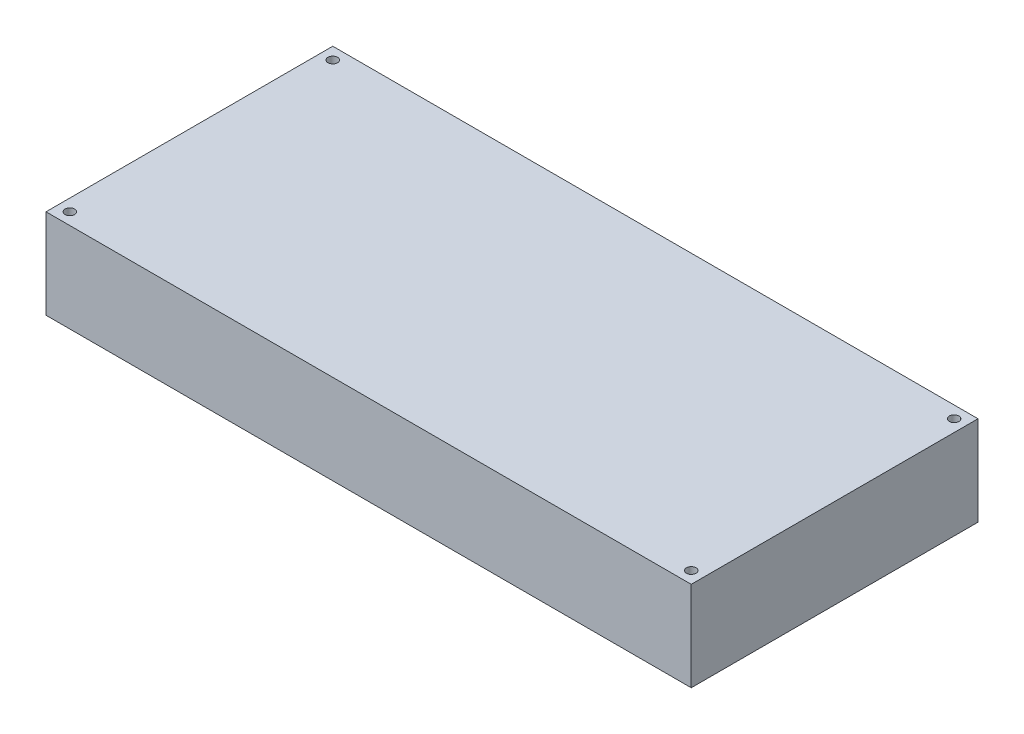
SolidWorks part; units mm, degrees
ref_plane "前视基准面" through (0, 0, 0) normal (0, 0, 1) x (1, 0, 0)
ref_plane "上视基准面" through (0, 0, 0) normal (0, 1, 0) x (1, 0, 0)
ref_plane "右视基准面" through (0, 0, 0) normal (1, 0, 0) x (0, 0, -1)
sketch "草图1" plane through (0, 0, 0) normal (0, 1, 0) x (1, 0, 0)
  line L0 (0, 0) -> (0, -29.456) construction
  line L1 (-54, 24) -> (54, 24)
  line L2 (-54, 24) -> (-54, -24)
  line L3 (-54, -24) -> (54, -24)
  line L4 (54, 24) -> (54, -24)
  line L5 (-54, 24) -> (54, -24) construction
  line L6 (-54, -24) -> (54, 24) construction
  line L7 (0, 0) -> (-48.2443, 0) construction
  circle A0 centre (-52, 22) radius 0.803
  circle A1 centre (-52, -22) radius 0.803
  circle A2 centre (52, -22) radius 0.803
  circle A3 centre (52, 22) radius 0.803
  point P0 (0, 0)
  dimension "D1" = 2
  dimension "D2" = 2
  dimension "D3" = 108
  dimension "D4" = 48
extrude "凸台-拉伸1" add sketch "草图1" along normal blind 15
